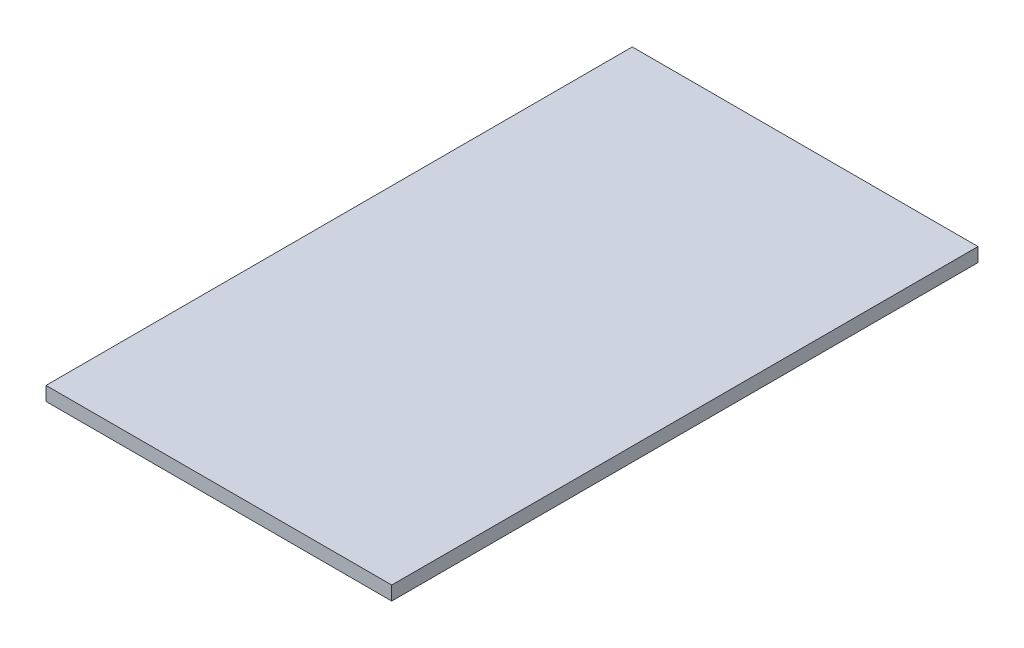
SolidWorks part; units mm, degrees
material "Acrylic (Medium-high impact)"
ref_plane "Front Plane" through (0, 0, 0) normal (0, 0, 1) x (1, 0, 0)
ref_plane "Top Plane" through (0, 0, 0) normal (0, 1, 0) x (1, 0, 0)
ref_plane "Right Plane" through (0, 0, 0) normal (1, 0, 0) x (0, 0, -1)
sketch "Sketch1" plane through (0, 0, 0) normal (0, 1, 0) x (1, 0, 0)
  line L1 (24.3296, 0) -> (182.0636, 0)
  line L2 (24.3296, 0) -> (24.3296, 267.462)
  line L3 (24.3296, 267.462) -> (182.0636, 267.462)
  line L4 (182.0636, 0) -> (182.0636, 267.462)
  line L7 (138.8836, 224.282) -> (29.4096, 224.282) construction
  line L8 (29.4096, 224.282) -> (29.4096, 195.58) construction
  dimension "D1" = 43.18
  dimension "D2" = 5.08
extrude "Extrude1" add sketch "Sketch1" along normal blind 6.35
